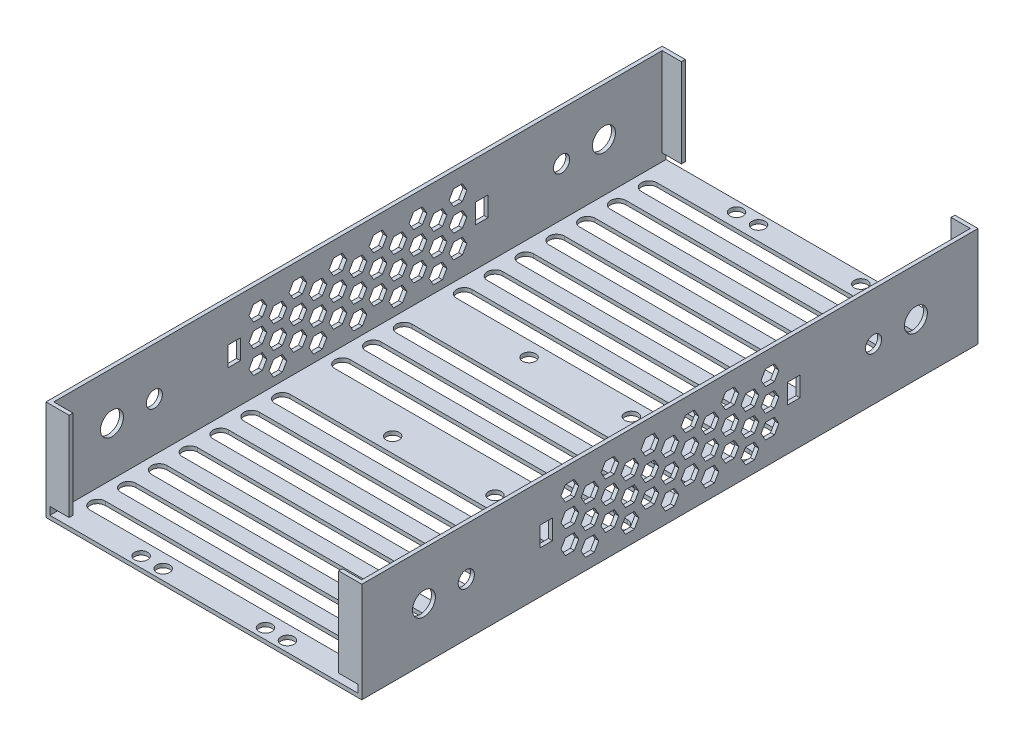
SolidWorks part; units mm, degrees
ref_plane "前视基准面" through (0, 0, 0) normal (0, 0, 1) x (1, 0, 0)
ref_plane "上视基准面" through (0, 0, 0) normal (0, 1, 0) x (1, 0, 0)
ref_plane "右视基准面" through (0, 0, 0) normal (1, 0, 0) x (0, 0, -1)
sketch "草图1" plane through (0, 0, 0) normal (0, 1, 0) x (1, 0, 0)
  line L10 (-40, 80) -> (40, 80)
  line L11 (40, 80) -> (40, -80)
  line L14 (-40, 80) -> (-40, -80)
  line L15 (-40, -80) -> (0, -80)
  line L16 (0, -80) -> (40, -80)
  line L17 (-55, 0) -> (55, 0) construction
  line L18 (0, -55) -> (0, 55) construction
  circle A1 centre (-13.2842, -77.2949) radius 1.7
  circle A2 centre (-13.2842, -17.7064) radius 1.7
  circle A3 centre (-13.2842, 77.2949) radius 1.7
  circle A4 centre (-13.2842, 17.7064) radius 1.7
  circle A5 centre (13.2842, -77.2949) radius 1.7
  circle A6 centre (13.2842, -17.7064) radius 1.7
  circle A7 centre (13.2842, 17.7064) radius 1.7
  circle A8 centre (13.2842, 77.2949) radius 1.7
  circle A10 centre (19, -77.3) radius 1.7
  circle A11 centre (-19, -77.3) radius 1.7
  circle A12 centre (19, 77.3) radius 1.7
  circle A13 centre (-19, 77.3) radius 1.7
  point P6 (0, -80)
extrude "凸台-拉伸1" add sketch "草图1" along normal blind 1 from offset 1
sketch "草图3" plane through (40, 0, 0) normal (1, 0, 0) x (0, 0, -1)
  line L5 (0, 0.55) -> (0, -0.55) construction
  line L8 (-33.759, 12.0422) -> (-30.5136, 12.0422)
  line L9 (-33.759, 12.0422) -> (-33.759, 17.1591)
  line L10 (-33.759, 17.1591) -> (-30.5136, 17.1591)
  line L11 (-30.5136, 12.0422) -> (-30.5136, 17.1591)
  line L14 (80, 1) -> (80, 27)
  line L17 (-80, 27) -> (80, 27)
  line L19 (-80, 27) -> (-80, 1)
  line L20 (-80, 1) -> (80, 1)
  line L25 (33.759, 12.0422) -> (30.5136, 12.0422)
  line L26 (30.5136, 12.0422) -> (30.5136, 17.1591)
  line L27 (33.759, 17.1591) -> (30.5136, 17.1591)
  line L28 (33.759, 12.0422) -> (33.759, 17.1591)
  circle A1 centre (-63.8734, 14.5998) radius 2.98
  circle A3 centre (-52.8734, 14.5998) radius 2.1
  circle A7 centre (52.8734, 14.5998) radius 2.1
  circle A8 centre (63.8734, 14.5998) radius 2.98
extrude "凸台-拉伸2" add sketch "草图3" along normal blind 1
sketch "草图11" plane through (-40, 0, -40) normal (1, 0, 0) x (0, 0, -1)
  line L5 (-40, 14.3) -> (-40, -14.3) construction
  line L8 (-73.759, 12.0422) -> (-70.5136, 12.0422)
  line L9 (-73.759, 12.0422) -> (-73.759, 17.1591)
  line L10 (-73.759, 17.1591) -> (-70.5136, 17.1591)
  line L11 (-70.5136, 12.0422) -> (-70.5136, 17.1591)
  line L21 (-70.5136, 12.0422) -> (-70.5136, 17.1591) construction
  line L22 (-73.759, 12.0422) -> (-70.5136, 12.0422) construction
  line L23 (40, 27) -> (40, 1)
  line L24 (40, 1) -> (-120, 1)
  line L25 (-120, 1) -> (-120, 27)
  line L26 (40, 27) -> (-120, 27)
  line L27 (-6.241, 12.0422) -> (-9.4864, 12.0422)
  line L28 (-9.4864, 12.0422) -> (-9.4864, 17.1591)
  line L29 (-6.241, 17.1591) -> (-9.4864, 17.1591)
  line L30 (-6.241, 12.0422) -> (-6.241, 17.1591)
  circle A1 centre (-103.8734, 14.5998) radius 2.98
  circle A3 centre (-92.8734, 14.5998) radius 2.1
  circle A6 centre (12.8734, 14.5998) radius 2.1
  circle A7 centre (23.8734, 14.5998) radius 2.98
extrude "凸台-拉伸3" add sketch "草图11" against normal blind 1
sketch "草图12" plane through (0, 0, 0) normal (0, 1, 0) x (1, 0, 0)
  line L0 (36, 63.6059) -> (-36, 63.6059) construction
  line L1 (36, 0) -> (-36, 0) construction
  line L2 (36, 61.6059) -> (-36, 61.6059)
  line L3 (36, 71.6059) -> (-36, 71.6059) construction
  line L4 (36, -2) -> (-36, -2)
  line L5 (36, 65.6059) -> (-36, 65.6059)
  line L6 (36, 69.6059) -> (-36, 69.6059)
  line L7 (36, 73.6059) -> (-36, 73.6059)
  line L8 (36, 55.6059) -> (-36, 55.6059) construction
  line L9 (36, 53.6059) -> (-36, 53.6059)
  line L10 (36, 57.6059) -> (-36, 57.6059)
  line L11 (36, 47.6059) -> (-36, 47.6059) construction
  line L12 (36, 45.6059) -> (-36, 45.6059)
  line L13 (36, 49.6059) -> (-36, 49.6059)
  line L14 (36, 39.6059) -> (-36, 39.6059) construction
  line L15 (36, 37.6059) -> (-36, 37.6059)
  line L16 (36, 41.6059) -> (-36, 41.6059)
  line L17 (36, 31.6059) -> (-36, 31.6059) construction
  line L18 (36, 29.6059) -> (-36, 29.6059)
  line L19 (36, 33.6059) -> (-36, 33.6059)
  line L20 (36, 23.6059) -> (-36, 23.6059) construction
  line L21 (36, 21.6059) -> (-36, 21.6059)
  line L22 (36, 25.6059) -> (-36, 25.6059)
  line L24 (36, -63.6059) -> (-36, -63.6059) construction
  line L25 (36, -61.6059) -> (-36, -61.6059)
  line L26 (36, -65.6059) -> (-36, -65.6059)
  line L27 (36, -71.6059) -> (-36, -71.6059) construction
  line L28 (36, -69.6059) -> (-36, -69.6059)
  line L29 (36, -73.6059) -> (-36, -73.6059)
  line L30 (36, -55.6059) -> (-36, -55.6059) construction
  line L31 (36, -53.6059) -> (-36, -53.6059)
  line L32 (36, -57.6059) -> (-36, -57.6059)
  line L33 (36, -47.6059) -> (-36, -47.6059) construction
  line L34 (36, -45.6059) -> (-36, -45.6059)
  line L35 (36, -49.6059) -> (-36, -49.6059)
  line L36 (36, -39.6059) -> (-36, -39.6059) construction
  line L37 (36, -37.6059) -> (-36, -37.6059)
  line L38 (36, -41.6059) -> (-36, -41.6059)
  line L39 (36, -31.6059) -> (-36, -31.6059) construction
  line L40 (36, -29.6059) -> (-36, -29.6059)
  line L41 (36, -33.6059) -> (-36, -33.6059)
  line L42 (36, -23.6059) -> (-36, -23.6059) construction
  line L43 (36, -21.6059) -> (-36, -21.6059)
  line L44 (36, -25.6059) -> (-36, -25.6059)
  line L45 (36, 2) -> (-36, 2)
  line L46 (36, -8) -> (-36, -8) construction
  line L47 (36, -10) -> (-36, -10)
  line L48 (36, -6) -> (-36, -6)
  line L49 (36, 8) -> (-36, 8) construction
  line L50 (36, 6) -> (-36, 6)
  line L51 (36, 10) -> (-36, 10)
  arc A0 (36, 69.6059) -> (36, 73.6059) centre (36, 71.6059) ccw
  arc A1 (-36, 73.6059) -> (-36, 69.6059) centre (-36, 71.6059) ccw
  arc A2 (36, 61.6059) -> (36, 65.6059) centre (36, 63.6059) ccw
  arc A3 (-36, 65.6059) -> (-36, 61.6059) centre (-36, 63.6059) ccw
  arc A4 (36, 53.6059) -> (36, 57.6059) centre (36, 55.6059) ccw
  arc A5 (-36, 57.6059) -> (-36, 53.6059) centre (-36, 55.6059) ccw
  arc A6 (36, 45.6059) -> (36, 49.6059) centre (36, 47.6059) ccw
  arc A7 (-36, 49.6059) -> (-36, 45.6059) centre (-36, 47.6059) ccw
  arc A8 (36, 37.6059) -> (36, 41.6059) centre (36, 39.6059) ccw
  arc A9 (-36, 41.6059) -> (-36, 37.6059) centre (-36, 39.6059) ccw
  arc A10 (36, 29.6059) -> (36, 33.6059) centre (36, 31.6059) ccw
  arc A11 (-36, 33.6059) -> (-36, 29.6059) centre (-36, 31.6059) ccw
  arc A12 (36, 21.6059) -> (36, 25.6059) centre (36, 23.6059) ccw
  arc A13 (-36, 25.6059) -> (-36, 21.6059) centre (-36, 23.6059) ccw
  arc A14 (36, -61.6059) -> (36, -65.6059) centre (36, -63.6059) cw
  arc A15 (-36, -65.6059) -> (-36, -61.6059) centre (-36, -63.6059) cw
  arc A16 (36, -69.6059) -> (36, -73.6059) centre (36, -71.6059) cw
  arc A17 (-36, -73.6059) -> (-36, -69.6059) centre (-36, -71.6059) cw
  arc A18 (36, -53.6059) -> (36, -57.6059) centre (36, -55.6059) cw
  arc A19 (-36, -57.6059) -> (-36, -53.6059) centre (-36, -55.6059) cw
  arc A20 (36, -45.6059) -> (36, -49.6059) centre (36, -47.6059) cw
  arc A21 (-36, -49.6059) -> (-36, -45.6059) centre (-36, -47.6059) cw
  arc A22 (36, -37.6059) -> (36, -41.6059) centre (36, -39.6059) cw
  arc A23 (-36, -41.6059) -> (-36, -37.6059) centre (-36, -39.6059) cw
  arc A24 (36, -29.6059) -> (36, -33.6059) centre (36, -31.6059) cw
  arc A25 (-36, -33.6059) -> (-36, -29.6059) centre (-36, -31.6059) cw
  arc A26 (36, -21.6059) -> (36, -25.6059) centre (36, -23.6059) cw
  arc A27 (-36, -25.6059) -> (-36, -21.6059) centre (-36, -23.6059) cw
  arc A28 (36, -2) -> (36, 2) centre (36, 0) ccw
  arc A29 (-36, 2) -> (-36, -2) centre (-36, 0) ccw
  arc A30 (36, -10) -> (36, -6) centre (36, -8) ccw
  arc A31 (-36, -6) -> (-36, -10) centre (-36, -8) ccw
  arc A32 (36, 6) -> (36, 10) centre (36, 8) ccw
  arc A33 (-36, 10) -> (-36, 6) centre (-36, 8) ccw
  point P0 (0, 0)
  point P3 (0, 63.6059)
  point P5 (0, 71.6059)
  point P18 (0, 55.6059)
  point P25 (0, 47.6059)
  point P32 (0, 39.6059)
  point P39 (0, 31.6059)
  point P46 (0, 23.6059)
  point P56 (0, -63.6059)
  point P63 (0, -71.6059)
  point P70 (0, -55.6059)
  point P77 (0, -47.6059)
  point P84 (0, -39.6059)
  point P91 (0, -31.6059)
  point P98 (0, -23.6059)
  point P105 (0, -8)
  point P112 (0, 8)
  dimension "D1" = 7
extrude "切除-拉伸1" cut sketch "草图12" along normal blind 10
sketch "草图14" plane through (0, 0, 80) normal (0, 0, 1) x (1, 0, 0)
  line L0 (0, -14.3) -> (0, 14.3) construction
  line L1 (-40, 27) -> (-40, 2) construction
  line L2 (-40, 27) -> (-35, 27)
  line L3 (-35, 27) -> (-35, 4)
  line L4 (-35, 4) -> (-40, 4)
  line L5 (-40, 27) -> (-40, 4)
  line L6 (40, 27) -> (40, 4)
  line L7 (35, 4) -> (40, 4)
  line L8 (35, 27) -> (35, 4)
  line L9 (40, 27) -> (35, 27)
extrude "凸台-拉伸4" add sketch "草图14" against normal blind 1
sketch "草图15" plane through (0, 0, -80) normal (0, 0, -1) x (-1, 0, 0)
  line L0 (-40, 27) -> (-35, 27)
  line L1 (-35, 27) -> (-35, 4)
  line L2 (-35, 4) -> (-40, 4)
  line L3 (-40, 4) -> (-40, 27)
  line L4 (40, 4) -> (35, 4)
  line L5 (35, 4) -> (35, 27)
  line L6 (35, 27) -> (40, 27)
  line L7 (40, 27) -> (40, 4)
extrude "凸台-拉伸5" add sketch "草图15" against normal blind 1
sketch "草图17" plane through (41, 0, 0) normal (1, 0, 0) x (0, 0, -1)
  line L19 (12.7017, 6) -> (11.547, 8)
  line L20 (11.547, 8) -> (9.2376, 8)
  line L21 (9.2376, 8) -> (8.0829, 6)
  line L22 (8.0829, 6) -> (9.2376, 4)
  line L23 (9.2376, 4) -> (11.547, 4)
  line L24 (11.547, 4) -> (12.7017, 6)
  line L25 (17.8979, 9) -> (16.7432, 11)
  line L26 (16.7432, 11) -> (14.4338, 11)
  line L27 (14.4338, 11) -> (13.2791, 9)
  line L28 (13.2791, 9) -> (14.4338, 7)
  line L29 (14.4338, 7) -> (16.7432, 7)
  line L30 (16.7432, 7) -> (17.8979, 9)
  line L31 (23.094, 12) -> (21.9393, 14)
  line L32 (21.9393, 14) -> (19.6299, 14)
  line L33 (19.6299, 14) -> (18.4752, 12)
  line L34 (18.4752, 12) -> (19.6299, 10)
  line L35 (19.6299, 10) -> (21.9393, 10)
  line L36 (21.9393, 10) -> (23.094, 12)
  line L37 (28.2902, 15) -> (27.1355, 17)
  line L38 (27.1355, 17) -> (24.8261, 17)
  line L39 (24.8261, 17) -> (23.6714, 15)
  line L40 (23.6714, 15) -> (24.8261, 13)
  line L41 (24.8261, 13) -> (27.1355, 13)
  line L42 (27.1355, 13) -> (28.2902, 15)
  line L49 (2.3094, 6) -> (1.1547, 8)
  line L50 (1.1547, 8) -> (-1.1547, 8)
  line L51 (-1.1547, 8) -> (-2.3094, 6)
  line L52 (-2.3094, 6) -> (-1.1547, 4)
  line L53 (-1.1547, 4) -> (1.1547, 4)
  line L54 (1.1547, 4) -> (2.3094, 6)
  line L55 (7.5056, 9) -> (6.3509, 11)
  line L56 (6.3509, 11) -> (4.0415, 11)
  line L57 (4.0415, 11) -> (2.8868, 9)
  line L58 (2.8868, 9) -> (4.0415, 7)
  line L59 (4.0415, 7) -> (6.3509, 7)
  line L60 (6.3509, 7) -> (7.5056, 9)
  line L61 (12.7017, 12) -> (11.547, 14)
  line L62 (11.547, 14) -> (9.2376, 14)
  line L63 (9.2376, 14) -> (8.0829, 12)
  line L64 (8.0829, 12) -> (9.2376, 10)
  line L65 (9.2376, 10) -> (11.547, 10)
  line L66 (11.547, 10) -> (12.7017, 12)
  line L67 (17.8979, 15) -> (16.7432, 17)
  line L68 (16.7432, 17) -> (14.4338, 17)
  line L69 (14.4338, 17) -> (13.2791, 15)
  line L70 (13.2791, 15) -> (14.4338, 13)
  line L71 (14.4338, 13) -> (16.7432, 13)
  line L72 (16.7432, 13) -> (17.8979, 15)
  line L73 (23.094, 18) -> (21.9393, 20)
  line L74 (21.9393, 20) -> (19.6299, 20)
  line L75 (19.6299, 20) -> (18.4752, 18)
  line L76 (18.4752, 18) -> (19.6299, 16)
  line L77 (19.6299, 16) -> (21.9393, 16)
  line L78 (21.9393, 16) -> (23.094, 18)
  line L91 (2.3094, 12) -> (1.1547, 14)
  line L92 (1.1547, 14) -> (-1.1547, 14)
  line L93 (-1.1547, 14) -> (-2.3094, 12)
  line L94 (-2.3094, 12) -> (-1.1547, 10)
  line L95 (-1.1547, 10) -> (1.1547, 10)
  line L96 (1.1547, 10) -> (2.3094, 12)
  line L97 (7.5056, 15) -> (6.3509, 17)
  line L98 (6.3509, 17) -> (4.0415, 17)
  line L99 (4.0415, 17) -> (2.8868, 15)
  line L100 (2.8868, 15) -> (4.0415, 13)
  line L101 (4.0415, 13) -> (6.3509, 13)
  line L102 (6.3509, 13) -> (7.5056, 15)
  line L103 (12.7017, 18) -> (11.547, 20)
  line L104 (11.547, 20) -> (9.2376, 20)
  line L105 (9.2376, 20) -> (8.0829, 18)
  line L106 (8.0829, 18) -> (9.2376, 16)
  line L107 (9.2376, 16) -> (11.547, 16)
  line L108 (11.547, 16) -> (12.7017, 18)
  line L109 (17.8979, 21) -> (16.7432, 23)
  line L110 (16.7432, 23) -> (14.4338, 23)
  line L111 (14.4338, 23) -> (13.2791, 21)
  line L112 (13.2791, 21) -> (14.4338, 19)
  line L113 (14.4338, 19) -> (16.7432, 19)
  line L114 (16.7432, 19) -> (17.8979, 21)
  line L133 (2.3094, 18) -> (1.1547, 20)
  line L134 (1.1547, 20) -> (-1.1547, 20)
  line L135 (-1.1547, 20) -> (-2.3094, 18)
  line L136 (-2.3094, 18) -> (-1.1547, 16)
  line L137 (-1.1547, 16) -> (1.1547, 16)
  line L138 (1.1547, 16) -> (2.3094, 18)
  line L139 (7.5056, 21) -> (6.3509, 23)
  line L140 (6.3509, 23) -> (4.0415, 23)
  line L141 (4.0415, 23) -> (2.8868, 21)
  line L142 (2.8868, 21) -> (4.0415, 19)
  line L143 (4.0415, 19) -> (6.3509, 19)
  line L144 (6.3509, 19) -> (7.5056, 21)
  line L191 (7.5056, 27) -> (6.3509, 29) [skipped]
  line L192 (6.3509, 29) -> (4.0415, 29) [skipped]
  line L193 (4.0415, 29) -> (2.8868, 27) [skipped]
  line L194 (2.8868, 27) -> (4.0415, 25) [skipped]
  line L195 (4.0415, 25) -> (6.3509, 25) [skipped]
  line L196 (6.3509, 25) -> (7.5056, 27) [skipped]
  line L197 (2.3094, 24) -> (1.1547, 26) [skipped]
  line L198 (1.1547, 26) -> (-1.1547, 26) [skipped]
  line L199 (-1.1547, 26) -> (-2.3094, 24) [skipped]
  line L200 (-2.3094, 24) -> (-1.1547, 22) [skipped]
  line L201 (-1.1547, 22) -> (1.1547, 22) [skipped]
  line L202 (1.1547, 22) -> (2.3094, 24) [skipped]
  line L203 (12.7017, 24) -> (11.547, 26) [skipped]
  line L204 (11.547, 26) -> (9.2376, 26) [skipped]
  line L205 (9.2376, 26) -> (8.0829, 24) [skipped]
  line L206 (8.0829, 24) -> (9.2376, 22) [skipped]
  line L207 (9.2376, 22) -> (11.547, 22) [skipped]
  line L208 (11.547, 22) -> (12.7017, 24) [skipped]
  line L209 (-8.0829, 18) -> (-9.2376, 20) [skipped]
  line L210 (-9.2376, 20) -> (-11.547, 20) [skipped]
  line L211 (-11.547, 20) -> (-12.7017, 18) [skipped]
  line L212 (-12.7017, 18) -> (-11.547, 16) [skipped]
  line L213 (-11.547, 16) -> (-9.2376, 16) [skipped]
  line L214 (-9.2376, 16) -> (-8.0829, 18) [skipped]
  line L215 (-2.8868, 21) -> (-4.0415, 23) [skipped]
  line L216 (-4.0415, 23) -> (-6.3509, 23) [skipped]
  line L217 (-6.3509, 23) -> (-7.5056, 21) [skipped]
  line L218 (-7.5056, 21) -> (-6.3509, 19) [skipped]
  line L219 (-6.3509, 19) -> (-4.0415, 19) [skipped]
  line L220 (-4.0415, 19) -> (-2.8868, 21) [skipped]
  line L221 (-2.8868, 15) -> (-4.0415, 17) [skipped]
  line L222 (-4.0415, 17) -> (-6.3509, 17) [skipped]
  line L223 (-6.3509, 17) -> (-7.5056, 15) [skipped]
  line L224 (-7.5056, 15) -> (-6.3509, 13) [skipped]
  line L225 (-6.3509, 13) -> (-4.0415, 13) [skipped]
  line L226 (-4.0415, 13) -> (-2.8868, 15) [skipped]
  line L227 (28.2902, 21) -> (27.1355, 23)
  line L228 (27.1355, 23) -> (24.8261, 23)
  line L229 (24.8261, 23) -> (23.6714, 21)
  line L230 (23.6714, 21) -> (24.8261, 19)
  line L231 (24.8261, 19) -> (27.1355, 19)
  line L232 (27.1355, 19) -> (28.2902, 21)
  line L233 (0, 14.3) -> (0, -14.3) construction
  line L234 (-27.1355, 7) -> (-28.2902, 9)
  line L235 (-24.8261, 7) -> (-27.1355, 7)
  line L236 (-23.6714, 9) -> (-24.8261, 7)
  line L237 (-24.8261, 11) -> (-23.6714, 9)
  line L238 (-27.1355, 11) -> (-24.8261, 11)
  line L239 (-28.2902, 9) -> (-27.1355, 11)
  line L240 (-21.9393, 4) -> (-23.094, 6)
  line L241 (-19.6299, 4) -> (-21.9393, 4)
  line L242 (-18.4752, 6) -> (-19.6299, 4)
  line L243 (-19.6299, 8) -> (-18.4752, 6)
  line L244 (-21.9393, 8) -> (-19.6299, 8)
  line L252 (23.094, 6) -> (21.9393, 8)
  line L253 (21.9393, 8) -> (19.6299, 8)
  line L254 (19.6299, 8) -> (18.4752, 6)
  line L255 (18.4752, 6) -> (19.6299, 4)
  line L256 (19.6299, 4) -> (21.9393, 4)
  line L257 (21.9393, 4) -> (23.094, 6)
  line L258 (28.2902, 9) -> (27.1355, 11)
  line L259 (27.1355, 11) -> (24.8261, 11)
  line L260 (24.8261, 11) -> (23.6714, 9)
  line L261 (23.6714, 9) -> (24.8261, 7)
  line L262 (24.8261, 7) -> (27.1355, 7)
  line L263 (27.1355, 7) -> (28.2902, 9)
  line L300 (-23.094, 6) -> (-21.9393, 8)
  line L301 (-27.1355, 19) -> (-28.2902, 21)
  line L302 (-24.8261, 19) -> (-27.1355, 19)
  line L303 (-23.6714, 21) -> (-24.8261, 19)
  line L304 (-24.8261, 23) -> (-23.6714, 21)
  line L305 (-27.1355, 23) -> (-24.8261, 23)
  line L306 (-28.2902, 21) -> (-27.1355, 23)
  line L307 (-6.3509, 19) -> (-7.5056, 21)
  line L308 (-4.0415, 19) -> (-6.3509, 19)
  line L309 (-2.8868, 21) -> (-4.0415, 19)
  line L310 (-4.0415, 23) -> (-2.8868, 21)
  line L311 (-6.3509, 23) -> (-4.0415, 23)
  line L312 (23.094, 0) -> (21.9393, 2) [skipped]
  line L313 (21.9393, 2) -> (19.6299, 2) [skipped]
  line L314 (19.6299, 2) -> (18.4752, 0) [skipped]
  line L315 (18.4752, 0) -> (19.6299, -2) [skipped]
  line L316 (19.6299, -2) -> (21.9393, -2) [skipped]
  line L317 (21.9393, -2) -> (23.094, 0) [skipped]
  line L318 (33.4863, 6) -> (32.3316, 8) [skipped]
  line L319 (32.3316, 8) -> (30.0222, 8) [skipped]
  line L320 (30.0222, 8) -> (28.8675, 6) [skipped]
  line L321 (28.8675, 6) -> (30.0222, 4) [skipped]
  line L322 (30.0222, 4) -> (32.3316, 4) [skipped]
  line L323 (32.3316, 4) -> (33.4863, 6) [skipped]
  line L324 (33.4863, 12) -> (32.3316, 14) [skipped]
  line L325 (32.3316, 14) -> (30.0222, 14) [skipped]
  line L326 (30.0222, 14) -> (28.8675, 12) [skipped]
  line L327 (28.8675, 12) -> (30.0222, 10) [skipped]
  line L328 (30.0222, 10) -> (32.3316, 10) [skipped]
  line L329 (32.3316, 10) -> (33.4863, 12) [skipped]
  line L330 (38.6825, 9) -> (37.5278, 11) [skipped]
  line L331 (37.5278, 11) -> (35.2184, 11) [skipped]
  line L332 (35.2184, 11) -> (34.0637, 9) [skipped]
  line L333 (34.0637, 9) -> (35.2184, 7) [skipped]
  line L334 (35.2184, 7) -> (37.5278, 7) [skipped]
  line L335 (37.5278, 7) -> (38.6825, 9) [skipped]
  line L336 (28.2902, 3) -> (27.1355, 5) [skipped]
  line L337 (27.1355, 5) -> (24.8261, 5) [skipped]
  line L338 (24.8261, 5) -> (23.6714, 3) [skipped]
  line L339 (23.6714, 3) -> (24.8261, 1) [skipped]
  line L340 (24.8261, 1) -> (27.1355, 1) [skipped]
  line L341 (27.1355, 1) -> (28.2902, 3) [skipped]
  line L342 (-7.5056, 21) -> (-6.3509, 23)
  line L439 (17.8979, 3) -> (16.7432, 5) [skipped]
  line L440 (16.7432, 5) -> (14.4338, 5) [skipped]
  line L441 (14.4338, 5) -> (13.2791, 3) [skipped]
  line L442 (13.2791, 3) -> (14.4338, 1) [skipped]
  line L443 (14.4338, 1) -> (16.7432, 1) [skipped]
  line L444 (16.7432, 1) -> (17.8979, 3) [skipped]
  line L445 (-16.7432, 19) -> (-17.8979, 21)
  line L446 (-14.4338, 19) -> (-16.7432, 19)
  line L447 (-13.2791, 21) -> (-14.4338, 19)
  line L448 (-14.4338, 23) -> (-13.2791, 21)
  line L449 (-16.7432, 23) -> (-14.4338, 23)
  line L450 (-17.8979, 21) -> (-16.7432, 23)
  line L451 (-11.547, 16) -> (-12.7017, 18)
  line L452 (-9.2376, 16) -> (-11.547, 16)
  line L453 (-8.0829, 18) -> (-9.2376, 16)
  line L454 (-9.2376, 20) -> (-8.0829, 18)
  line L455 (-11.547, 20) -> (-9.2376, 20)
  line L456 (-12.7017, 18) -> (-11.547, 20)
  line L457 (-6.3509, 13) -> (-7.5056, 15)
  line L458 (-4.0415, 13) -> (-6.3509, 13)
  line L459 (-2.8868, 15) -> (-4.0415, 13)
  line L460 (-4.0415, 17) -> (-2.8868, 15)
  line L461 (-6.3509, 17) -> (-4.0415, 17)
  line L462 (-7.5056, 15) -> (-6.3509, 17)
  line L463 (-21.9393, 16) -> (-23.094, 18)
  line L464 (-19.6299, 16) -> (-21.9393, 16)
  line L465 (-18.4752, 18) -> (-19.6299, 16)
  line L466 (-19.6299, 20) -> (-18.4752, 18)
  line L467 (-21.9393, 20) -> (-19.6299, 20)
  line L468 (-23.094, 18) -> (-21.9393, 20)
  line L469 (-16.7432, 13) -> (-17.8979, 15)
  line L470 (-14.4338, 13) -> (-16.7432, 13)
  line L471 (-13.2791, 15) -> (-14.4338, 13)
  line L472 (-14.4338, 17) -> (-13.2791, 15)
  line L473 (-16.7432, 17) -> (-14.4338, 17)
  line L474 (-17.8979, 15) -> (-16.7432, 17)
  line L475 (-11.547, 10) -> (-12.7017, 12)
  line L476 (-9.2376, 10) -> (-11.547, 10)
  line L477 (-8.0829, 12) -> (-9.2376, 10)
  line L478 (-9.2376, 14) -> (-8.0829, 12)
  line L479 (-11.547, 14) -> (-9.2376, 14)
  line L480 (-12.7017, 12) -> (-11.547, 14)
  line L481 (-6.3509, 7) -> (-7.5056, 9)
  line L482 (-4.0415, 7) -> (-6.3509, 7)
  line L483 (-2.8868, 9) -> (-4.0415, 7)
  line L484 (-4.0415, 11) -> (-2.8868, 9)
  line L485 (-6.3509, 11) -> (-4.0415, 11)
  line L486 (-7.5056, 9) -> (-6.3509, 11)
  line L487 (-27.1355, 13) -> (-28.2902, 15)
  line L488 (-24.8261, 13) -> (-27.1355, 13)
  line L489 (-23.6714, 15) -> (-24.8261, 13)
  line L490 (-24.8261, 17) -> (-23.6714, 15)
  line L491 (-27.1355, 17) -> (-24.8261, 17)
  line L492 (-28.2902, 15) -> (-27.1355, 17)
  line L493 (-21.9393, 10) -> (-23.094, 12)
  line L494 (-19.6299, 10) -> (-21.9393, 10)
  line L495 (-18.4752, 12) -> (-19.6299, 10)
  line L496 (-19.6299, 14) -> (-18.4752, 12)
  line L497 (-21.9393, 14) -> (-19.6299, 14)
  line L498 (-23.094, 12) -> (-21.9393, 14)
  line L499 (-16.7432, 7) -> (-17.8979, 9)
  line L500 (-14.4338, 7) -> (-16.7432, 7)
  line L501 (-13.2791, 9) -> (-14.4338, 7)
  line L502 (-14.4338, 11) -> (-13.2791, 9)
  line L503 (-16.7432, 11) -> (-14.4338, 11)
  line L504 (-17.8979, 9) -> (-16.7432, 11)
  line L505 (-11.547, 4) -> (-12.7017, 6)
  line L506 (-9.2376, 4) -> (-11.547, 4)
  line L507 (-8.0829, 6) -> (-9.2376, 4)
  line L508 (-9.2376, 8) -> (-8.0829, 6)
  line L509 (-11.547, 8) -> (-9.2376, 8)
  line L510 (-12.7017, 6) -> (-11.547, 8)
  circle A1 centre (-5.1962, 21) radius 2 construction
  circle A2 centre (10.3923, 6) radius 2 construction
  circle A3 centre (15.5885, 9) radius 2 construction
  circle A4 centre (20.7846, 12) radius 2 construction
  circle A5 centre (25.9808, 15) radius 2 construction
  circle A7 centre (0, 6) radius 2 construction
  circle A8 centre (5.1962, 9) radius 2 construction
  circle A9 centre (10.3923, 12) radius 2 construction
  circle A10 centre (15.5885, 15) radius 2 construction
  circle A11 centre (20.7846, 18) radius 2 construction
  circle A14 centre (0, 12) radius 2 construction
  circle A15 centre (5.1962, 15) radius 2 construction
  circle A16 centre (10.3923, 18) radius 2 construction
  circle A17 centre (15.5885, 21) radius 2 construction
  circle A21 centre (0, 18) radius 2 construction
  circle A22 centre (5.1962, 21) radius 2 construction
  circle A29 centre (-15.5885, 21) radius 2 construction
  circle A30 centre (-5.1962, 15) radius 2 construction
  circle A31 centre (-10.3923, 18) radius 2 construction
  circle A32 centre (-5.1962, 21) radius 2 construction
  circle A33 centre (-10.3923, 18) radius 2 construction
  circle A34 centre (-5.1962, 15) radius 2 construction
  circle A35 centre (-20.7846, 18) radius 2 construction
  circle A36 centre (0, 24) radius 2 construction
  circle A37 centre (5.1962, 27) radius 2 construction
  circle A38 centre (10.3923, 24) radius 2 construction
  circle A39 centre (-15.5885, 15) radius 2 construction
  circle A40 centre (-10.3923, 12) radius 2 construction
  circle A41 centre (-5.1962, 9) radius 2 construction
  circle A42 centre (-25.9808, 15) radius 2 construction
  circle A43 centre (-20.7846, 12) radius 2 construction
  circle A44 centre (-15.5885, 9) radius 2 construction
  circle A45 centre (-10.3923, 6) radius 2 construction
  dimension "D2" = 5
  dimension "D1" = 3
extrude "切除-拉伸2" cut sketch "草图17" against normal through all
